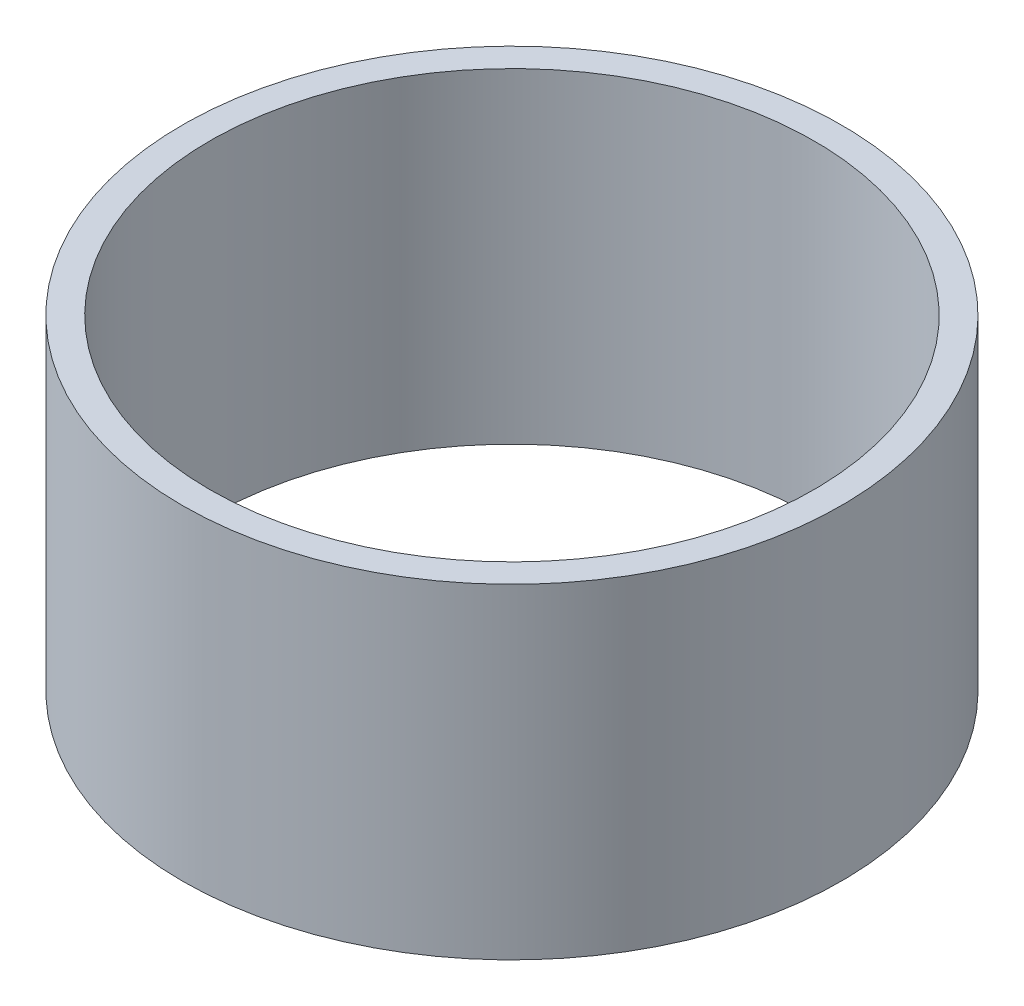
SolidWorks part; units mm, degrees
material "6061-T6 (SS)"
ref_plane "Front Plane" through (0, 0, 0) normal (0, 0, 1) x (1, 0, 0)
ref_plane "Top Plane" through (0, 0, 0) normal (0, 1, 0) x (1, 0, 0)
ref_plane "Right Plane" through (0, 0, 0) normal (1, 0, 0) x (0, 0, -1)
sketch "Sketch1" plane through (0, 0, 0) normal (0, 1, 0) x (1, 0, 0)
  circle A0 centre (0, 0) radius 76.2
  circle A1 centre (0, 0) radius 69.85
  dimension "D1" = 152.4
  dimension "D2" = 6.35
extrude "Boss-Extrude1" add sketch "Sketch1" along normal mid plane 75.2094
